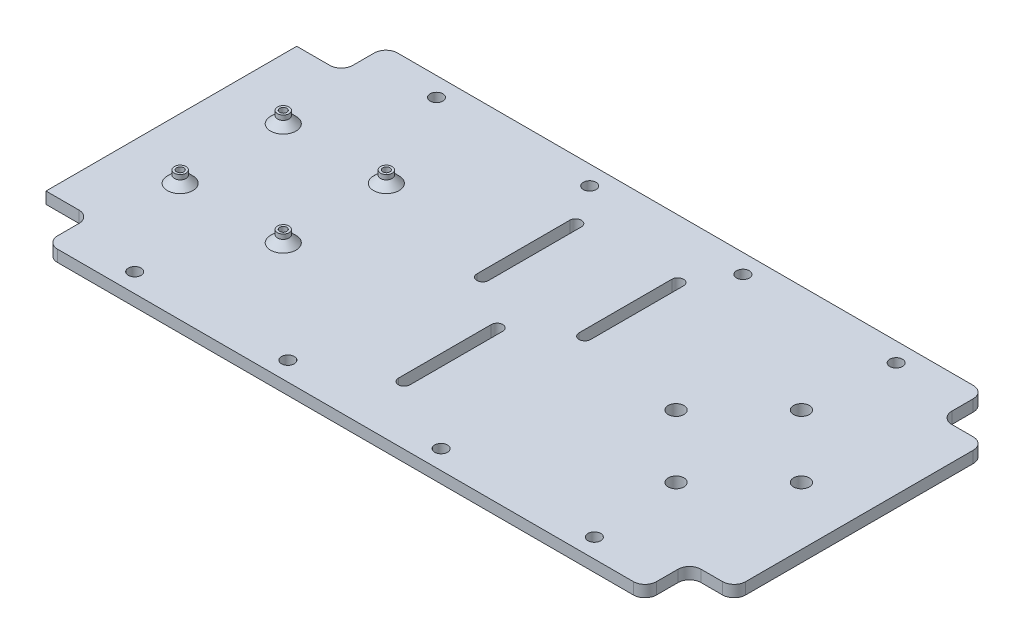
SolidWorks part; units mm, degrees
ref_plane "Ebene vorne" through (0, 0, 0) normal (1, 0, 0) x (0, 1, 0)
ref_plane "Ebene oben" through (0, 0, 0) normal (0, 0, 1) x (0, 1, 0)
ref_plane "Ebene rechts" through (0, 0, 0) normal (0, 1, 0) x (-1, 0, 0)
sketch "Skizze1" plane through (0, 20, 0) normal (0, 1, 0) x (1, 0, 0)
  line L0 (-148.2, -55) -> (-148.2, 55) construction
  line L6 (-131.8, -75) -> (-148.2, -75) construction
  line L7 (-129, 73.2) -> (129, 73.2)
  line L8 (-129, 73.2) -> (-129, -73.2)
  line L9 (-129, -73.2) -> (129, -73.2)
  line L10 (129, 73.2) -> (129, -73.2)
  line L15 (129, -54) -> (148.2, -54)
  line L16 (129, -54) -> (129, 54)
  line L17 (129, 54) -> (148.2, 54)
  line L18 (148.2, -54) -> (148.2, 54)
  line L19 (-129, 54) -> (-148.2, 54)
  line L20 (-129, 54) -> (-129, -54)
  line L21 (-129, -54) -> (-148.2, -54)
  line L22 (-148.2, 54) -> (-148.2, -54)
  point P25 (-129, 0)
  dimension "D1" = 19.2
  dimension "D2" = 277.2
  dimension "D3" = 296.4
  dimension "D4" = 1.8
  dimension "D5" = 21
  dimension "D6" = 75
extrude "Aufsatz-Linear austragen1" add sketch "Skizze1" along normal blind 5
other "Fläche löschen2" [suppressed]
surface "Oberfläche-Offset1" parameters "D1"=0
sketch "Skizze2" plane through (-97, 0, 0) normal (1, 0, 0) x (0, 1, 0)
  line L0 (20, 52) -> (14, 52)
  line L1 (20, 54) -> (20, -54) construction
  line L2 (14, 52) -> (12, 50)
  line L3 (12, 50) -> (12, -50)
  line L4 (12, -50) -> (14, -52)
  line L5 (14, -52) -> (20, -52)
  line L6 (20, -73.2) -> (20, -54) construction
  line L7 (20, -52) -> (20, 52)
  line L8 (1.8, 55) -> (18.2, 55) construction
  point P10 (20, 0)
  point P13 (12, 0)
  dimension "D1" = 45
  dimension "D2" = 6
  dimension "D3" = 8
  dimension "D4" = 3
extrude "Aufsatz-Linear austragen2" add sketch "Skizze2" against normal blind 2
fillet "Verrundung1" radius 5 4 edges at (-99, 20, 0) (-97, 20, 0) (-98, 20, -52) (-98, 20, 52)
pattern_linear "Lineares Muster1" count 5 spacing 49 along (1, 0, 0) of "Aufsatz-Linear austragen2", "Verrundung1"
delete or keep bodies "Körper-Löschen/beibehalten 1" type delete bodies bodies 107 108 109 104 105 106
fillet "Verrundung2" radius 5 10 edges at (-129, 22.5, -54) (-129, 22.5, -73.2) (129, 22.5, -73.2) (129, 22.5, -54) (148.2, 22.5, -54) (148.2, 22.5, 54) (129, 22.5, 54) (129, 22.5, 73.2) (-129, 22.5, 73.2) (-129, 22.5, 54)
sketch "Skizze3" plane through (0, 25, 0) normal (0, 1, 0) x (-1, 0, 0)
  line L0 (0, 27.9106) -> (-22, -27.9106) construction
  line L1 (-22, -27.9106) -> (22, -27.9106) construction
  line L2 (22, -27.9106) -> (0, 27.9106) construction
  line L3 (0, 27.9106) -> (0, 0) construction
  line L4 (0, 0) -> (0, -27.9106) construction
  line L5 (0, 7.9106) -> (0, 47.9106) construction
  line L6 (-2.5, 7.9106) -> (-2.5, 47.9106)
  line L7 (2.5, 7.9106) -> (2.5, 47.9106)
  line L8 (-22, -47.9106) -> (-22, -7.9106) construction
  line L9 (-24.5, -47.9106) -> (-24.5, -7.9106)
  line L10 (-19.5, -47.9106) -> (-19.5, -7.9106)
  line L11 (22, -47.9106) -> (22, -7.9106) construction
  line L12 (19.5, -47.9106) -> (19.5, -7.9106)
  line L13 (24.5, -47.9106) -> (24.5, -7.9106)
  arc A0 (-2.5, 7.9106) -> (2.5, 7.9106) centre (0, 7.9106) ccw
  arc A1 (2.5, 47.9106) -> (-2.5, 47.9106) centre (0, 47.9106) ccw
  arc A2 (-24.5, -47.9106) -> (-19.5, -47.9106) centre (-22, -47.9106) ccw
  arc A3 (-19.5, -7.9106) -> (-24.5, -7.9106) centre (-22, -7.9106) ccw
  arc A4 (19.5, -47.9106) -> (24.5, -47.9106) centre (22, -47.9106) ccw
  arc A5 (24.5, -7.9106) -> (19.5, -7.9106) centre (22, -7.9106) ccw
  point P8 (0, 27.9106)
  point P15 (-22, -27.9106)
  point P22 (22, -27.9106)
  dimension "D1" = 60
  dimension "D2" = 44
  dimension "D3" = 5
  dimension "D4" = 40
extrude "Schnitt-Linear austragen1" cut sketch "Skizze3" against normal through all both and the other way through all
sketch "Skizze4" plane through (0, 20, 0) normal (0, -1, 0) x (1, 0, 0)
  line L1 (-13.4553, 50.4106) -> (10.5458, 50.4106)
  line L2 (-13.4553, 50.4106) -> (-13.4553, 5.4106)
  line L3 (-13.4553, 5.4106) -> (10.5458, 5.4106)
  line L4 (10.5458, 50.4106) -> (10.5458, 5.4106)
  arc A0 (-1, 5.6193) -> (1, 5.6193) centre (0, 7.9106) ccw construction
  arc A1 (-1, 50.2019) -> (1, 50.2019) centre (0, 47.9106) ccw construction
extrude "Schnitt-Linear austragen5" cut sketch "Skizze4" along normal up to surface (8 mm away) up to face at (0, 12, -22.2425)
sketch "Skizze5" plane through (0, 12, 0) normal (0, -1, 0) x (1, 0, 0)
  line L0 (0, 47.9106) -> (0, 7.9106) construction
  line L1 (6.4768, 47.9106) -> (6.4768, 7.9106)
  line L2 (-6.4768, 47.9106) -> (-6.4768, 7.9106)
  arc A0 (6.4768, 47.9106) -> (-6.4768, 47.9106) centre (0, 47.9106) ccw
  arc A1 (-6.4768, 7.9106) -> (6.4768, 7.9106) centre (0, 7.9106) ccw
  point P4 (0, 27.9106)
extrude "Schnitt-Linear austragen6" cut sketch "Skizze5" against normal up to surface (8 mm away)
sketch "Skizze6" plane through (0, 20, 0) normal (0, -1, 0) x (1, 0, 0)
  line L1 (-28.2464, 92.5197) -> (16.914, 92.5197)
  line L2 (-28.2464, 92.5197) -> (-28.2464, 35.6886)
  line L3 (-28.2464, 35.6886) -> (16.914, 35.6886)
  line L4 (16.914, 92.5197) -> (16.914, 35.6886)
extrude "Schnitt-Linear austragen7" cut sketch "Skizze6" along normal through all
sketch "Skizze7" plane through (0, 27, 0) normal (0, 1, 0) x (1, 0, 0)
  circle A0 centre (96.2009, -27) radius 3.4 construction
  circle A1 centre (96.2009, 27) radius 3.4 construction
  circle A2 centre (96.2009, -27) radius 3.4
  circle A3 centre (96.2009, 27) radius 3.4
extrude "Schnitt-Linear austragen8" cut sketch "Skizze7" against normal through all both and the other way through all
sketch "Skizze8" plane through (0, 20, 0) normal (0, -1, 0) x (1, 0, 0)
  circle A0 centre (96.2009, 27) radius 10
  circle A1 centre (96.2009, -27) radius 10
  dimension "D1" = 20
extrude "Schnitt-Linear austragen9" cut sketch "Skizze8" along normal blind 20
sketch "Skizze9" plane through (0, 25, 0) normal (0, 1, 0) x (1, 0, 0)
  circle A0 centre (-77.8, -22.2) radius 1.5 construction
  circle A1 centre (-77.8, 22.2) radius 1.5 construction
  circle A2 centre (-122.2, 22.2) radius 1.5 construction
  circle A3 centre (-122.2, -22.2) radius 1.5 construction
  circle A4 centre (-77.8, -22.2) radius 1.5
  circle A5 centre (-77.8, 22.2) radius 1.5
  circle A6 centre (-122.2, 22.2) radius 1.5
  circle A7 centre (-122.2, -22.2) radius 1.5
sketch "Skizze10" plane through (0, 25, 0) normal (0, 1, 0) x (-1, 0, 0)
  circle A0 centre (122.2, 22.2) radius 1.55
  circle A1 centre (122.2, -22.2) radius 1.55
  circle A2 centre (77.8, -22.2) radius 1.55
  circle A3 centre (77.8, 22.2) radius 1.55
  circle A4 centre (77.8, 22.2) radius 2.5
  circle A5 centre (122.2, 22.2) radius 2.5
  circle A6 centre (122.2, -22.2) radius 2.5
  circle A7 centre (77.8, -22.2) radius 2.5
  dimension "D1" = 3.1
  dimension "D2" = 5
extrude "Aufsatz-Linear austragen3" add sketch "Skizze10" along normal blind 5
sketch "Skizze11" plane through (0, 30, 0) normal (0, 1, 0) x (-1, 0, 0)
  circle A0 centre (122.2, -22.2) radius 1.55 construction
  circle A1 centre (77.8, -22.2) radius 1.55 construction
  circle A2 centre (122.2, 22.2) radius 1.55 construction
  circle A3 centre (77.8, 22.2) radius 1.55 construction
  circle A4 centre (122.2, -22.2) radius 1.55
  circle A5 centre (77.8, -22.2) radius 1.55
  circle A6 centre (122.2, 22.2) radius 1.55
  circle A7 centre (77.8, 22.2) radius 1.55
extrude "Schnitt-Linear austragen10" cut sketch "Skizze11" against normal through all
sketch "Skizze12" plane through (0, 25, 0) normal (0, 1, 0) x (-1, 0, 0)
  line L0 (-96.2009, 27) -> (-96.2009, -27) construction
  line L1 (-123.2009, 0) -> (-69.2009, 0) construction
  circle A0 centre (-123.2009, 0) radius 3.4
  circle A1 centre (-69.2009, 0) radius 3.4
  circle A2 centre (-96.2009, 27) radius 3.4 construction
  point P6 (-96.2009, 0)
extrude "Schnitt-Linear austragen11" cut sketch "Skizze12" against normal through all
sketch "Skizze13" [suppressed] plane through (0, 25, 0) normal (0, 1, 0) x (-1, 0, 0)
  line L0 (-83.09, 42.5552) -> (-83.09, -24.5494) construction
  line L1 (83.09, 41.4322) -> (83.09, -17.9513) construction
  line L2 (-28.5894, 55.875) -> (50.9442, 55.875) construction
  line L3 (-17.8459, -55.875) -> (52.8684, -55.875) construction
  line L4 (-83.09, 6.1676) -> (-148.2, 6.1676) construction
  line L5 (-148.2, 49) -> (-148.2, -49) construction
  line L6 (83.09, 6.1676) -> (148.2, 6.1676) construction
  line L7 (148.2, -49) -> (148.2, 49) construction
  line L8 (-17.8459, 55.875) -> (-17.8459, 73.2) construction
  line L9 (124, 73.2) -> (-124, 73.2) construction
  line L10 (-3.4425, -55.875) -> (-3.4425, -73.2) construction
  line L11 (124, -73.2) -> (-124, -73.2) construction
  circle A0 centre (-73.44, 22.355) radius 4
  circle A1 centre (9.49, 27.435) radius 4
  circle A2 centre (10, -40.765) radius 4
  circle A3 centre (56.09, 14.105) radius 4
  dimension "D1" = 83.44
  dimension "D7" = 8
  dimension "D2" = 5.08
  dimension "D3" = 63.12
  dimension "D4" = 82.93
  dimension "D5" = 46.6
  dimension "D6" = 13.33
  dimension "D8" = 27
  dimension "D9" = 9.65
  dimension "D10" = 15.11
  dimension "D11" = 28.44
extrude "Aufsatz-Linear austragen4" [suppressed] add sketch "Skizze13" along normal blind 10
sketch "Skizze14" [suppressed] plane through (0, 35, 0) normal (0, 1, 0) x (-1, 0, 0)
  circle A0 centre (-73.44, 22.355) radius 1.75
  circle A1 centre (9.49, 27.435) radius 1.75
  circle A2 centre (56.09, 14.105) radius 1.75
  circle A3 centre (10, -40.765) radius 1.75
  dimension "D1" = 3.5
extrude "Schnitt-Linear austragen12" [suppressed] cut sketch "Skizze14" against normal through all
chamfer "Fase1" [suppressed] distance 5 angle 45
sketch "Skizze15" [suppressed] plane through (0, 20, 0) normal (0, -1, 0) x (1, 0, 0)
  circle A0 centre (-56.09, 14.105) radius 5
  dimension "D1" = 10
extrude "Schnitt-Linear austragen13" [suppressed] cut sketch "Skizze15" along normal through all
sketch "Skizze16" plane through (0, 25, 0) normal (0, 1, 0) x (1, 0, 0)
  line L0 (-129, 65) -> (-99, 65) construction
  line L2 (150, -65) -> (-180.8036, -65) construction
  line L3 (150, -73.2) -> (150, -56.8) construction
  line L5 (-129, 68.2) -> (-129, 59) construction
  line L6 (129, 68.2) -> (129, 59) construction
  line L7 (129, 65) -> (130, 65) construction
  line L8 (130, 73.2) -> (130, 56.8) construction
  line L9 (-99, 65) -> (-33, 65) construction
  line L10 (-33, 65) -> (33, 65) construction
  line L11 (33, 65) -> (99, 65) construction
  line L12 (99, 65) -> (129, 65) construction
  circle A0 centre (-99, 65) radius 2.75
  circle A1 centre (-33, 65) radius 2.75
  circle A2 centre (33, 65) radius 2.75
  circle A3 centre (99, 65) radius 2.75
  dimension "D1" = 30
  dimension "D2" = 5.5
extrude "Schnitt-Linear austragen14" cut sketch "Skizze16" against normal through all
mirror "Spiegeln1" about plane through (0, 0, 0) normal (0, 0, 1) of "Schnitt-Linear austragen14"
chamfer "Fase2" distance 3 angle 45 4 edges at (-77.8, 25, -19.7) (-122.2, 25, -19.7) (-122.2, 25, 24.7) (-77.8, 25, 24.7)
